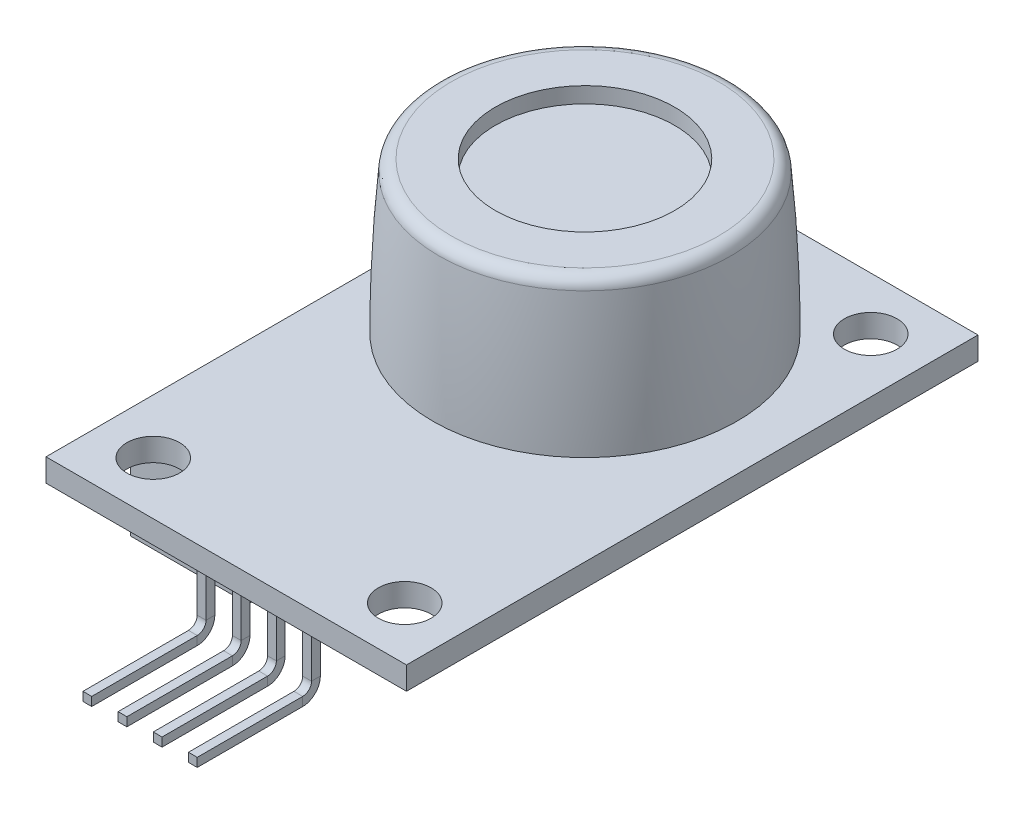
SolidWorks part; units mm, degrees
ref_plane "Спереди" through (0, 0, 0) normal (0, 0, 1) x (1, 0, 0)
ref_plane "Сверху" through (0, 0, 0) normal (0, 1, 0) x (1, 0, 0)
ref_plane "Справа" through (0, 0, 0) normal (1, 0, 0) x (0, 0, -1)
sketch "Эскиз1" plane through (0, 0, 0) normal (1, 0, 0) x (0, 0, -1)
  line L0 (0, 1.2) -> (-7.05, 1.2)
  line L1 (-7.05, 1.2) -> (-7.25, 1.4)
  line L2 (-7.25, 1.4) -> (-7.65, 1)
  line L3 (-7.65, 1) -> (-8.65, 1)
  line L4 (-7.6, 9.6) -> (-5.1, 9.6)
  line L5 (-5.1, 9.6) -> (-5.1, 8.7)
  line L6 (-5.1, 8.7) -> (0, 8.7)
  line L7 (0, 8.7) -> (0, 1.2)
  line L8 (0, 0) -> (0, 1.2) construction
  line L9 (-8.65, 1) -> (-8.65, 9.6) construction
  arc A0 (-8.65, 1) -> (-8.2973, 8.9619) centre (81.3821, 1) cw
  arc A1 (-8.2973, 8.9619) -> (-7.6, 9.6) centre (-7.6, 8.9) cw
  dimension "D1" = 5.1
  dimension "D10" = 0.7
  dimension "D2" = 8.65
  dimension "D3" = 8.6
  dimension "D4" = 0.9
  dimension "D5" = 0.2
  dimension "D6" = 135
  dimension "D7" = 1.4
  dimension "D8" = 1.2
  dimension "D9" = 1
  dimension "D11" = 7.6
revolve "Повернуть1" add sketch "Эскиз1" angle 360 about L7
sketch "Эскиз2" plane through (0, 1.2, 0) normal (0, -1, 0) x (1, 0, 0)
  line L0 (-4.3841, 4.3841) -> (4.3841, -4.3841) construction
  line L2 (4.3841, 4.3841) -> (-4.3841, -4.3841) construction
  line L3 (0, 0) -> (0, 6.2) construction
  circle A0 centre (0, 0) radius 6.2
  circle A1 centre (0, 0) radius 3.35
  arc A2 (-3.3764, -3.3764) -> (-3.3764, 3.3764) centre (0, 0) cw construction
  arc A3 (3.3764, -3.3764) -> (3.3764, 3.3764) centre (0, 0) ccw construction
  arc A4 (-4.3841, 4.3841) -> (-2.3688, 2.3688) centre (-3.3764, 3.3764) cw
  arc A5 (-4.3841, -4.3841) -> (-2.3688, -2.3688) centre (-3.3764, -3.3764) ccw
  arc A6 (4.3841, 4.3841) -> (2.3688, 2.3688) centre (3.3764, 3.3764) ccw
  arc A7 (4.3841, -4.3841) -> (2.3688, -2.3688) centre (3.3764, -3.3764) cw
  point P6 (0, 0)
  point P10 (0, 0)
  dimension "D1" = 45
  dimension "D2" = 12.4
  dimension "D3" = 6.7
extrude "Бобышка-Вытянуть1" add sketch "Эскиз2" along normal blind 1.2 contours A0 A5 A1 A4 | A7 A0 A6 A1
sketch "Эскиз3" plane through (0, 0, 0) normal (0, -1, 0) x (1, 0, 0)
  line L0 (0, 0) -> (-6.2, 0) construction
  line L1 (-3.3588, 3.3588) -> (0, 0) construction
  line L2 (-3.3588, -3.3588) -> (0, 0) construction
  line L3 (0, 0) -> (0, -7.05) construction
  arc A0 (-4.3841, 4.3841) -> (-4.3841, -4.3841) centre (0, 0) ccw construction
  arc A1 (-2.2149, -4.202) -> (-2.2149, 4.202) centre (0, 0) cw construction
  arc A4 (-4.3841, -4.3841) -> (-2.3688, -2.3688) centre (-3.3764, -3.3764) ccw construction
  arc A5 (-2.3688, 2.3688) -> (-4.3841, 4.3841) centre (-3.3764, 3.3764) ccw construction
  circle A6 centre (-4.75, 0) radius 0.5
  circle A7 centre (-3.3588, 3.3588) radius 0.5
  circle A8 centre (-3.3588, -3.3588) radius 0.5
  circle A9 centre (0, 0) radius 7.05 construction
  circle A10 centre (3.3588, 3.3588) radius 0.5
  circle A11 centre (4.75, 0) radius 0.5
  circle A12 centre (3.3588, -3.3588) radius 0.5
  dimension "D1" = 4.75
  dimension "D2" = 45
  dimension "D3" = 1
  dimension "D4" = 45
extrude "Бобышка-Вытянуть2" add sketch "Эскиз3" along normal blind 5.8
chamfer "Фаска1" distance 0.2 angle 45 6 edges at (3.3588, -5.8, 3.8588) (4.75, -5.8, 0.5) (3.3588, -5.8, -2.8588) (-3.3588, -5.8, -3.8588) (-4.75, -5.8, -0.5) (-3.3588, -5.8, 2.8588)
sketch "Sketch1" plane through (0, 0, 0) normal (0, -1, 0) x (1, 0, 0)
  line L0 (0, 20.4) -> (0, -12.1) construction
  line L2 (-7.15, 17.4) -> (7.15, 17.4) construction
  line L3 (-7.15, 17.4) -> (-7.15, -9.1) construction
  line L4 (10.25, 20.4) -> (-10.25, 20.4)
  line L5 (10.25, 20.4) -> (10.25, -12.1)
  line L6 (10.25, -12.1) -> (-10.25, -12.1)
  line L7 (-10.25, 20.4) -> (-10.25, -12.1)
  line L8 (-7.15, -9.1) -> (7.15, -9.1) construction
  line L9 (7.15, 17.4) -> (7.15, -9.1) construction
  line L10 (-7.15, 17.4) -> (7.15, -9.1) construction
  line L11 (-7.15, -9.1) -> (7.15, 17.4) construction
  circle A0 centre (-7.15, 17.4) radius 1.5
  circle A1 centre (7.15, 17.4) radius 1.5
  circle A2 centre (7.15, -9.1) radius 1.5
  circle A3 centre (-7.15, -9.1) radius 1.5
  point P2 (0, 4.15)
  point P5 (0, 0)
  dimension "D7" = 3
  dimension "D1" = 20.5
  dimension "D2" = 32.5
  dimension "D3" = 10.25
  dimension "D4" = 12.1
  dimension "D5" = 14.3
  dimension "D6" = 26.5
extrude "Boss-Extrude1" add sketch "Sketch1" along normal blind 1.3 separate body
sketch "Sketch2" plane through (0, -1.3, 0) normal (0, -1, 0) x (1, 0, 0)
  line L0 (-10.25, 20.4) -> (-10.25, -12.1) construction
  line L1 (-10.25, 15.6) -> (-3.55, 15.6)
  line L2 (-10.25, 15.6) -> (-10.25, 8.9)
  line L3 (-10.25, 8.9) -> (-3.55, 8.9)
  line L4 (-3.55, 15.6) -> (-3.55, 8.9)
  line L5 (10.25, 20.4) -> (-10.25, 20.4) construction
  dimension "D1" = 6.7
  dimension "D2" = 11.5
extrude "Boss-Extrude2" add sketch "Sketch2" along normal blind 5 separate body
sketch "Sketch3" plane through (0, 0, 0) normal (0, 1, 0) x (1, 0, 0)
  line L0 (-7.15, -18.9) -> (7.15, -18.9) construction
  line L1 (-1.15, -18.9) -> (-1.15, -18.4)
  line L2 (-3.15, -18.9) -> (-2.65, -18.9)
  line L3 (-3.15, -18.9) -> (-3.15, -18.4)
  line L4 (-3.15, -18.4) -> (-2.65, -18.4)
  line L5 (-2.65, -18.9) -> (-2.65, -18.4)
  line L6 (-1.15, -18.9) -> (-0.65, -18.9)
  line L7 (-0.65, -18.9) -> (-0.65, -18.4)
  line L8 (-1.15, -18.4) -> (-0.65, -18.4)
  line L9 (0.85, -18.9) -> (0.85, -18.4)
  line L10 (0.85, -18.9) -> (1.35, -18.9)
  line L11 (1.35, -18.9) -> (1.35, -18.4)
  line L12 (0.85, -18.4) -> (1.35, -18.4)
  line L13 (2.85, -18.9) -> (2.85, -18.4)
  line L14 (2.85, -18.9) -> (3.35, -18.9)
  line L15 (3.35, -18.9) -> (3.35, -18.4)
  line L16 (2.85, -18.4) -> (3.35, -18.4)
  circle A0 centre (-7.15, -17.4) radius 1.5 construction
  circle A1 centre (7.15, -17.4) radius 1.5 construction
  dimension "D1" = 0.5
  dimension "D2" = 4
  dimension "D3" = 4
sketch "Sketch4" plane through (-10.25, 0, 0) normal (-1, 0, 0) x (0, 0, 1)
  line L0 (18.4, 0) -> (18.4, -5)
  line L1 (18.9, 0) -> (18.4, 0) construction
  line L2 (20.4, 0) -> (-12.1, 0) construction
  line L3 (19.4, -6) -> (25.4, -6)
  arc A0 (18.4, -5) -> (19.4, -6) centre (19.4, -5) ccw
  point P9 (18.4, -6)
  dimension "D3" = 1
  dimension "D1" = 6
  dimension "D2" = 7
sweep "Sweep1" add profiles "Sketch3" path "Sketch4"
sketch "Sketch5" plane through (0, -6.3, 0) normal (0, -1, 0) x (1, 0, 0)
  line L0 (-6.9, 15.6) -> (-6.9, 8.9) construction
  line L1 (-3.55, 15.6) -> (-10.25, 15.6) construction
  line L2 (-10.25, 8.9) -> (-3.55, 8.9) construction
  circle A0 centre (-6.9, 12.25) radius 1.5
  dimension "D1" = 3
extrude "Cut-Extrude1" cut sketch "Sketch5" against normal blind 0.2
sketch "Sketch6" plane through (0, -6.1, 0) normal (0, -1, 0) x (1, 0, 0)
  line L0 (-6.9, 13.75) -> (-6.9, 10.75) construction
  line L1 (-6.9, 12.25) -> (-8.4, 12.25) construction
  line L2 (-6.9, 12.25) -> (-5.4, 12.25) construction
  line L3 (-6.86, 12.21) -> (-6.86, 10.7505)
  line L4 (-6.9374, 13.7495) -> (-6.86, 13.7495)
  line L5 (-6.9374, 13.7495) -> (-6.9374, 12.29)
  line L6 (-6.9374, 10.7505) -> (-6.86, 10.7505)
  line L7 (-6.86, 13.7495) -> (-6.86, 12.29)
  line L8 (-8.3995, 12.29) -> (-6.9374, 12.29)
  line L9 (-8.3995, 12.29) -> (-8.3995, 12.21)
  line L10 (-8.3995, 12.21) -> (-6.9374, 12.21)
  line L11 (-5.4005, 12.29) -> (-5.4005, 12.21)
  line L12 (-6.86, 12.29) -> (-5.4005, 12.29)
  line L13 (-6.86, 12.21) -> (-5.4005, 12.21)
  line L14 (-6.9374, 12.21) -> (-6.9374, 10.7505)
  circle A0 centre (-6.9, 12.25) radius 1.5 construction
  circle A1 centre (-6.9, 12.25) radius 1.5 construction
  dimension "D1" = 0.0374
  dimension "D2" = 0.04
  dimension "D3" = 0.04
  dimension "D4" = 0.04
extrude "Cut-Extrude2" cut sketch "Sketch6" against normal blind 0.2
